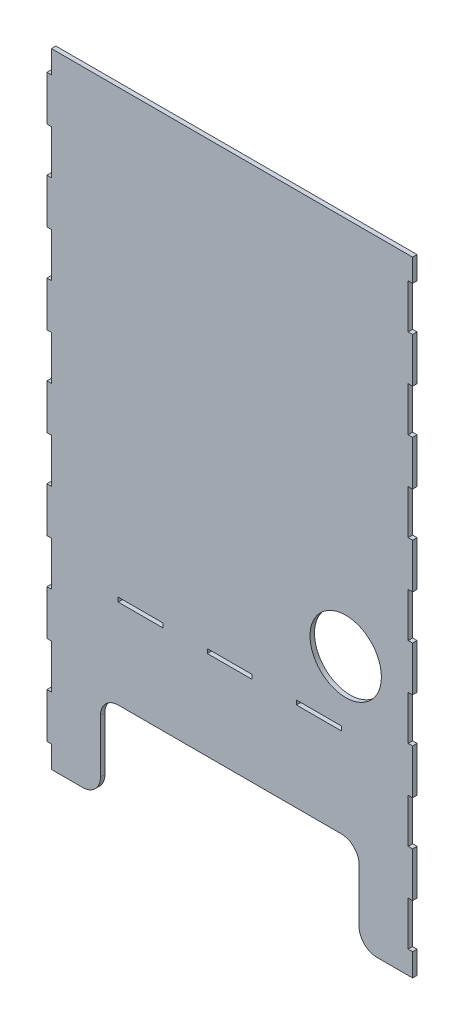
SolidWorks part; units mm, degrees
ref_plane "Ebene vorne" through (0, 0, 0) normal (0, 0, 1) x (1, 0, 0)
ref_plane "Ebene oben" through (0, 0, 0) normal (0, 1, 0) x (1, 0, 0)
ref_plane "Ebene rechts" through (0, 0, 0) normal (1, 0, 0) x (0, 0, -1)
sketch "Skizze1" plane through (0, 0, 0) normal (0, 0, 1) x (1, 0, 0)
  line L0 (0, 0) -> (0, 700)
  line L1 (0, 700) -> (410, 700)
  line L2 (410, 700) -> (410, 0)
  line L3 (410, 0) -> (370, 0)
  line L4 (0, 100) -> (410, 100) construction
  line L5 (60, 20) -> (60, 80)
  line L6 (350, 20) -> (350, 80)
  line L7 (330, 100) -> (80, 100)
  line L8 (40, 0) -> (0, 0)
  arc A0 (80, 100) -> (60, 80) centre (80, 80) ccw
  arc A1 (330, 100) -> (350, 80) centre (330, 80) cw
  arc A2 (40, 0) -> (60, 20) centre (40, 20) ccw
  arc A3 (370, 0) -> (350, 20) centre (370, 20) cw
  point P13 (60, 100)
  point P16 (350, 100)
  point P19 (60, 0)
  point P22 (350, 0)
  dimension "D4" = 20
  dimension "D5" = 20
  dimension "D8" = 20
  dimension "D9" = 20
  dimension "D1" = 700
  dimension "D2" = 410
  dimension "D3" = 100
  dimension "D6" = 60
  dimension "D7" = 60
extrude "Aufsatz-Linear austragen1" add sketch "Skizze1" along normal blind 5 contours L0 L1 L2 L3 A3 L6 A1 L7 A0 L5 A2 L8
sketch "Skizze2" plane through (0, 0, 5) normal (0, 0, 1) x (1, 0, 0)
  line L0 (0, 0) -> (0, 700) construction
  line L1 (79.95, 204.8) -> (130.25, 204.8)
  line L2 (79.95, 204.8) -> (79.95, 200)
  line L3 (79.95, 200) -> (130.25, 200)
  line L4 (130.25, 204.8) -> (130.25, 200)
  dimension "D1" = 50.3
  dimension "D2" = 4.8
  dimension "D3" = 79.95
  dimension "D4" = 200
extrude "Schnitt-Linear austragen1" cut sketch "Skizze2" against normal blind 5
pattern_linear "Lineares Muster1" count 3 spacing 99.9 along (1, 0, 0) of "Schnitt-Linear austragen1"
sketch "Skizze3" plane through (0, 0, 5) normal (0, 0, 1) x (1, 0, 0)
  line L0 (0, 700) -> (410, 700) construction
  line L1 (-87.9124, 674.5) -> (5, 674.5)
  line L2 (-87.9124, 674.5) -> (-87.9124, 724.1)
  line L3 (-87.9124, 724.1) -> (5, 724.1)
  line L4 (5, 674.5) -> (5, 724.1)
  dimension "D1" = 49.6
  dimension "D2" = 5
  dimension "D3" = 24.1
extrude "Schnitt-Linear austragen2" cut sketch "Skizze3" against normal blind 5
pattern_linear "Lineares Muster2" count 8 spacing 99.9 along (0, -1, 0) of "Schnitt-Linear austragen2"
ref_plane "Ebene1" through (205, 0, 0) normal (1, 0, 0) x (0, 0, -1)
mirror "Spiegeln2" [suppressed] about plane through (205, 0, 0) normal (1, 0, 0)
sketch "Skizze5" [suppressed] plane through (0, 0, 5) normal (0, 0, 1) x (1, 0, 0)
  line L1 (5, 50.3) -> (-32.3107, 50.3)
  line L2 (5, 50.3) -> (5, -36.4204)
  line L3 (5, -36.4204) -> (-32.3107, -36.4204)
  line L4 (-32.3107, 50.3) -> (-32.3107, -36.4204)
extrude "Schnitt-Linear austragen3" [suppressed] cut sketch "Skizze5" against normal blind 5
sketch "Skizze4" plane through (0, 0, 5) normal (0, 0, 1) x (1, 0, 0)
  line L1 (405, 674.5) -> (491.468, 674.5)
  line L2 (405, 674.5) -> (405, 624.9)
  line L3 (405, 624.9) -> (491.468, 624.9)
  line L4 (491.468, 674.5) -> (491.468, 624.9)
  line L5 (410, 700) -> (410, 0) construction
  dimension "D1" = 49.6
  dimension "D2" = 5
  dimension "D3" = 25.5
extrude "Schnitt-Linear austragen4" cut sketch "Skizze4" against normal blind 5
pattern_linear "Lineares Muster3" count 7 spacing 99.9 along (0, -1, 0) of "Schnitt-Linear austragen4"
sketch "Skizze6" [suppressed] plane through (0, 0, 5) normal (0, 0, 1) x (1, 0, 0)
  line L14 (130.25, -5) -> (130.25, 0)
  line L15 (130.25, 0) -> (79.95, 0)
  line L16 (79.95, 0) -> (79.95, -5)
  line L17 (79.95, -5) -> (130.25, -5)
  line L18 (230.15, -5) -> (230.15, 0)
  line L19 (230.15, 0) -> (179.85, 0)
  line L20 (179.85, 0) -> (179.85, -5)
  line L21 (179.85, -5) -> (230.15, -5)
  line L22 (330.05, -5) -> (330.05, 0)
  line L23 (330.05, 0) -> (279.75, 0)
  line L24 (279.75, 0) -> (279.75, -5)
  line L25 (279.75, -5) -> (330.05, -5)
  line L26 (405, 0) -> (405, -5)
  line L27 (5, 0) -> (5, -5)
sketch "Skizze8" plane through (0, 0, 5) normal (0, 0, 1) x (1, 0, 0)
  line L0 (405, 274.9) -> (405, 225.3) construction
  line L2 (330.05, 204.8) -> (279.75, 204.8) construction
  circle A0 centre (335, 274.8) radius 40
  dimension "D1" = 80
  dimension "D2" = 70
  dimension "D3" = 70
extrude "Schnitt-Linear austragen5" cut sketch "Skizze8" against normal blind 10
equation "\"D1@Ebene1\"=410/2"
